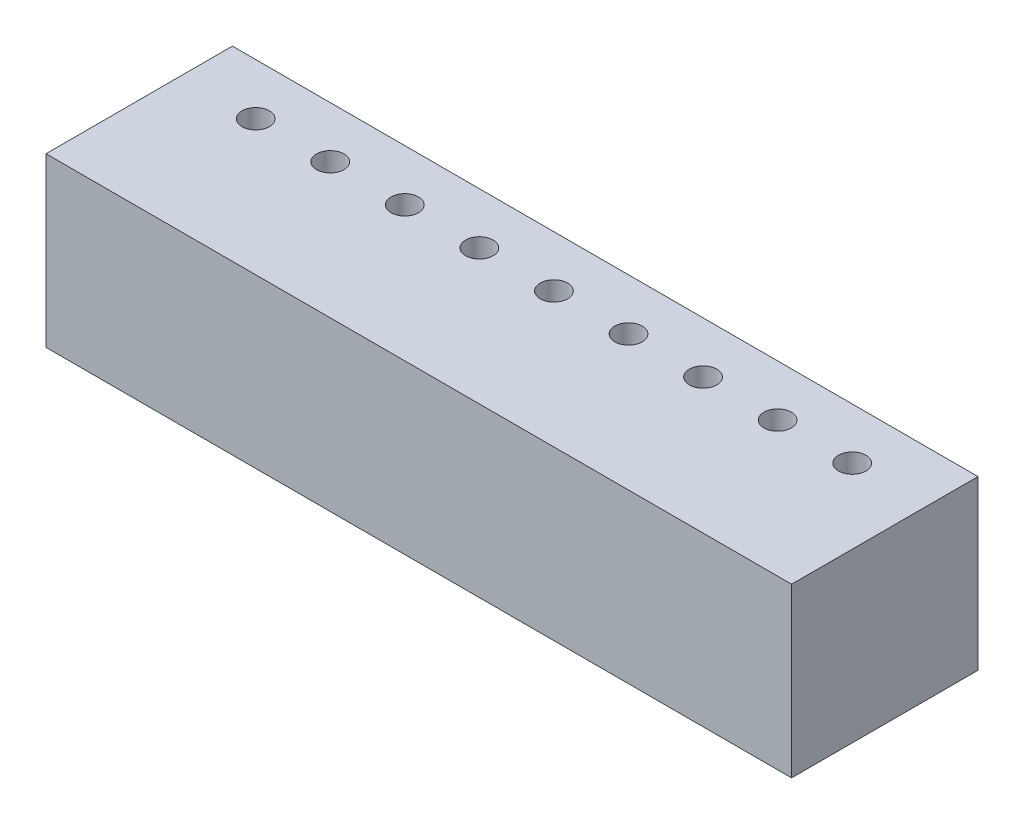
SolidWorks part; units mm, degrees
ref_plane "Front Plane" through (0, 0, 0) normal (0, 0, 1) x (1, 0, 0)
ref_plane "Top Plane" through (0, 0, 0) normal (0, 1, 0) x (1, 0, 0)
ref_plane "Right Plane" through (0, 0, 0) normal (1, 0, 0) x (0, 0, -1)
sketch "Sketch1" plane through (0, 0, 0) normal (0, 1, 0) x (1, 0, 0)
  line L1 (-11.5441, 14.1912) -> (28.4559, 14.1912)
  line L2 (-11.5441, 14.1912) -> (-11.5441, 4.1912)
  line L3 (-11.5441, 4.1912) -> (28.4559, 4.1912)
  line L4 (28.4559, 14.1912) -> (28.4559, 4.1912)
  circle A0 centre (24.4559, 11.4412) radius 0.7353
  circle A1 centre (20.4559, 11.4412) radius 0.7353
  circle A2 centre (16.4559, 11.4412) radius 0.7353
  circle A3 centre (12.4559, 11.4412) radius 0.7353
  circle A4 centre (8.4559, 11.4412) radius 0.7353
  circle A5 centre (4.4559, 11.4412) radius 0.7353
  circle A6 centre (0.4559, 11.4412) radius 0.7353
  circle A7 centre (-3.5441, 11.4412) radius 0.7353
  circle A8 centre (-7.5441, 11.4412) radius 0.7353
  dimension "D1" = 10
  dimension "D2" = 40
  dimension "D3" = 4
  dimension "D4" = 2.75
  dimension "D5" = 9
extrude "Boss-Extrude1" add sketch "Sketch1" along normal blind 9
